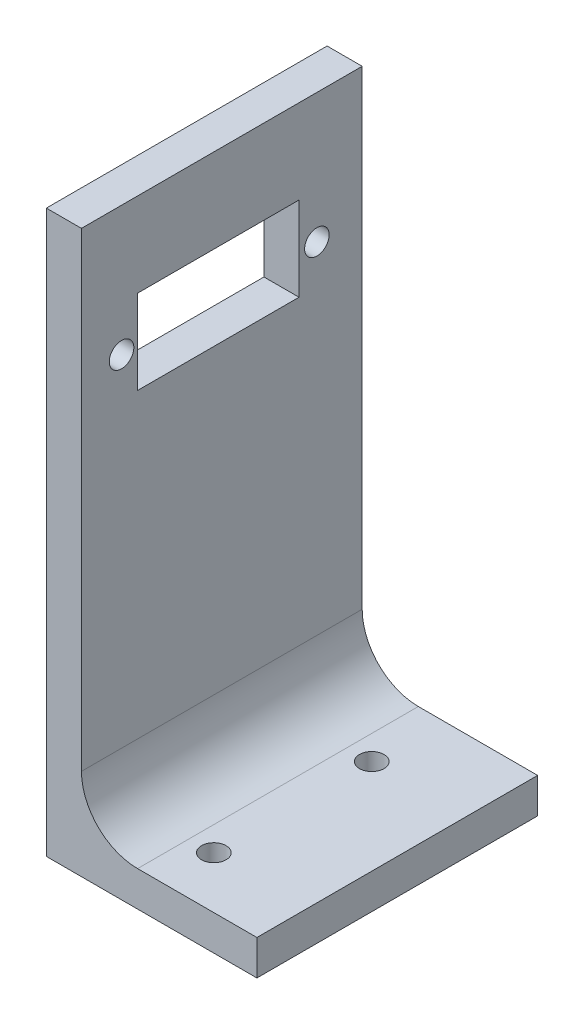
SolidWorks part; units mm, degrees
ref_plane "Plano frontal" through (0, 0, 0) normal (0, 0, 1) x (1, 0, 0)
ref_plane "Plano superior" through (0, 0, 0) normal (0, 1, 0) x (1, 0, 0)
ref_plane "Plano direito" through (0, 0, 0) normal (1, 0, 0) x (0, 0, -1)
sketch "Esboço1" plane through (0, 0, 0) normal (0, 0, 1) x (1, 0, 0)
  line L0 (-30, 40.0262) -> (-30, -39.9738)
  line L1 (-30, -39.9738) -> (0, -39.9738)
  line L2 (0, -39.9738) -> (0, -34.9738)
  line L3 (0, -34.9738) -> (-25, -34.9738)
  line L4 (-25, -34.9738) -> (-25, 40.0262)
  line L5 (-25, 40.0262) -> (-30, 40.0262)
  dimension "D1" = 80
  dimension "D3" = 5
  dimension "D4" = 30
extrude "Ressalto-extrusão1" add sketch "Esboço1" along normal blind 40 contours L4 L5 L0 L1 L2 L3
hole_wizard "Broca de rosquear para helicoide M31" positions "Esboço2" profile "Esboço3" hole size "M3x0.5" standard "Ansi Metric"
sketch "Esboço2" plane through (0, -34.9738, 0) normal (0, 1, 0) x (1, 0, 0)
  point P0 (-13.529, -32.6129)
  point P2 (-13.529, -10.1108)
sketch "Esboço3" plane through (-13.529, -34.9738, 32.6129) normal (1, 0, 0) x (0, 0, 1)
  line L0 (0, 0) -> (0, 11.0515)
  line L1 (0, 11.0515) -> (1.75, 10)
  line L2 (1.75, 10) -> (1.75, 0)
  line L5 (1.75, 0) -> (0, 0)
  line L10 (0, 11.0515) -> (-1.75, 10) construction
  line L11 (0, -6.35) -> (0, 107.95) construction
  dimension "Hole Dia." = 3.5
  dimension "Hole Depth" = 10
  dimension "Drill Angle" = 118
fillet "Filete1" radius 8 1 edges at (-25, -34.9738, 20)
sketch "Esboço6" plane through (-25, 0, 0) normal (1, 0, 0) x (0, 0, -1)
  line L0 (0, -26.9738) -> (0, 40.0262) construction
  line L1 (-9, 28.0262) -> (-32, 28.0262)
  line L2 (-9, 28.0262) -> (-9, 16.0262)
  line L3 (-9, 16.0262) -> (-32, 16.0262)
  line L4 (-32, 28.0262) -> (-32, 16.0262)
  line L5 (-40, -26.9738) -> (-40, 40.0262) construction
  line L6 (-40, 40.0262) -> (0, 40.0262) construction
  dimension "D1" = 23
  dimension "D2" = 12
  dimension "D3" = 9
  dimension "D4" = 90
  dimension "D5" = 12
extrude "Corte-extrusão1" cut sketch "Esboço6" against normal blind 10
hole_wizard "Broca de rosquear para helicoide M33" positions "Esboço7" profile "Esboço8" hole size "M3x0.5" standard "Ansi Metric"
sketch "Esboço7" plane through (-25, 0, 0) normal (1, 0, 0) x (0, 0, -1)
  point P0 (-6.4545, 21.5886)
  point P2 (-34.2853, 21.5886)
sketch "Esboço8" plane through (-25, 21.5886, 6.4545) normal (0, 1, 0) x (0, 0, -1)
  line L0 (0, 0) -> (0, 11.0515)
  line L1 (0, 11.0515) -> (1.75, 10)
  line L2 (1.75, 10) -> (1.75, 0)
  line L5 (1.75, 0) -> (0, 0)
  line L10 (0, 11.0515) -> (-1.75, 10) construction
  line L11 (0, -6.35) -> (0, 107.95) construction
  dimension "Hole Dia." = 3.5
  dimension "Hole Depth" = 10
  dimension "Drill Angle" = 118
